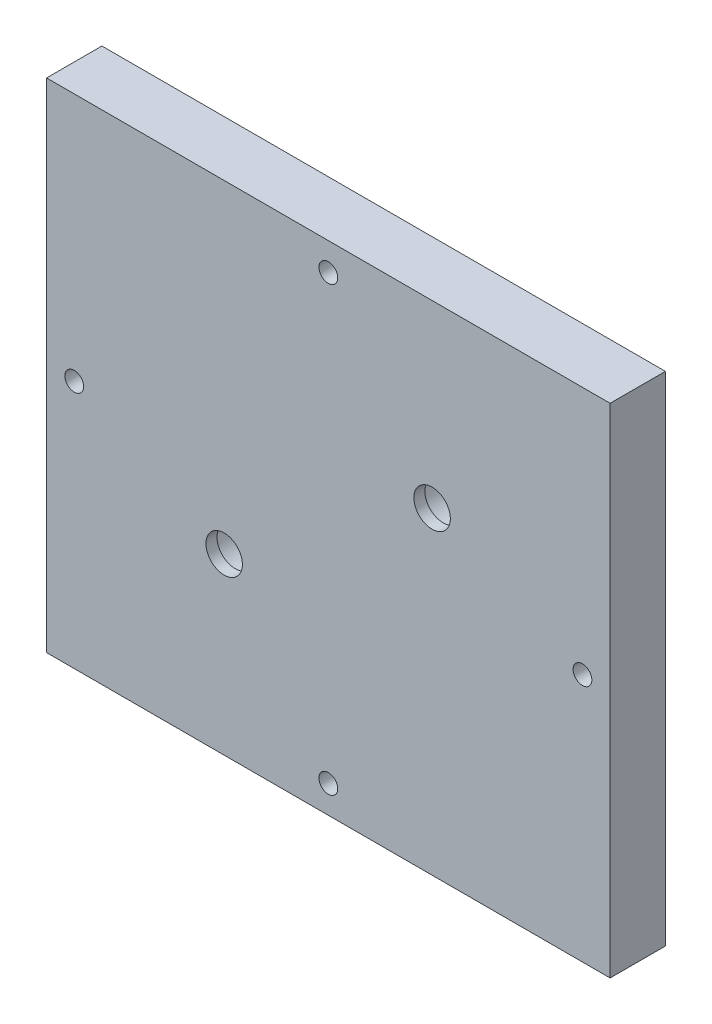
SolidWorks part; units mm, degrees
material "Náilon 6/10"
ref_plane "Plano frontal" through (0, 0, 0) normal (0, 0, 1) x (1, 0, 0)
ref_plane "Plano superior" through (0, 0, 0) normal (0, 1, 0) x (1, 0, 0)
ref_plane "Plano direito" through (0, 0, 0) normal (1, 0, 0) x (0, 0, -1)
sketch "Esboço1" plane through (0, 0, -23.335) normal (0, 0, 1) x (1, 0, 0)
  line L0 (83.7732, 103.8506) -> (-93.7536, 103.8506) construction
  line L1 (45.9632, 58.8506) -> (-55.9368, 58.8506)
  line L2 (45.9632, 58.8506) -> (45.9632, -31.1494)
  line L3 (45.9632, -31.1494) -> (-55.9368, -31.1494)
  line L4 (-55.9368, 58.8506) -> (-55.9368, -31.1494)
  line L5 (83.7732, -109.5762) -> (83.7732, 103.8506) construction
  dimension "D1" = 90
  dimension "D2" = 45
  dimension "D3" = 101.9
  dimension "D4" = 37.81
extrude "Ressalto-extrusão1" add sketch "Esboço1" along normal blind 10
hole_wizard "Furo com folga de M39" positions "Esboço10" profile "Esboço9" hole size "M3" standard "Métrico Ansi" end condition up to next
sketch "Esboço10" plane through (0, 0, -23.335) normal (0, 0, -1) x (-1, 0, 0)
  point P0 (-40.9632, 13.8506)
  point P1 (4.9868, 53.8506)
  point P4 (50.9368, 13.8506)
  point P7 (4.9868, -26.1494)
sketch "Esboço9" plane through (40.9632, 13.8506, -23.335) normal (1, 0, 0) x (0, 1, 0)
  line L0 (0, 0) -> (0, 10)
  line L1 (0, 10) -> (1.7, 10)
  line L2 (1.7, 10) -> (1.7, 0)
  line L5 (1.7, 0) -> (0, 0)
  line L11 (0, -6.35) -> (0, 107.95) construction
  dimension "Thru Hole Dia." = 3.4
  dimension "Thru Hole Depth" = 10
sketch "Esboço11" plane through (0, 0, -23.335) normal (0, 0, -1) x (-1, 0, 0)
  line L0 (-45.9632, 58.8506) -> (55.9368, 58.8506) construction
  line L1 (-45.9632, -31.1494) -> (-45.9632, 58.8506) construction
  line L2 (55.9368, 58.8506) -> (55.9368, -31.1494) construction
  circle A0 centre (-13.7732, 26.3306) radius 5
  circle A1 centre (23.8268, 0.3506) radius 5
  dimension "D1" = 10
  dimension "D2" = 10
  dimension "D3" = 32.52
  dimension "D4" = 32.19
  dimension "D5" = 58.5
  dimension "D6" = 32.11
extrude "Corte-extrusão1" cut sketch "Esboço11" against normal blind 8
hole_wizard "Furo com folga de M61" positions "Esboço13" profile "Esboço12" hole size "M6" standard "Métrico Ansi" end condition up to next
sketch "Esboço13" plane through (0, 0, -15.335) normal (0, 0, -1) x (-1, 0, 0)
  point P0 (-13.7732, 26.3306)
  point P1 (23.8268, 0.3506)
sketch "Esboço12" plane through (13.7732, 26.3306, -15.335) normal (1, 0, 0) x (0, 1, 0)
  line L0 (0, 0) -> (0, 2)
  line L1 (0, 2) -> (3.3, 2)
  line L2 (3.3, 2) -> (3.3, 0)
  line L5 (3.3, 0) -> (0, 0)
  line L11 (0, -6.35) -> (0, 107.95) construction
  dimension "Thru Hole Dia." = 6.6
  dimension "Thru Hole Depth" = 2
